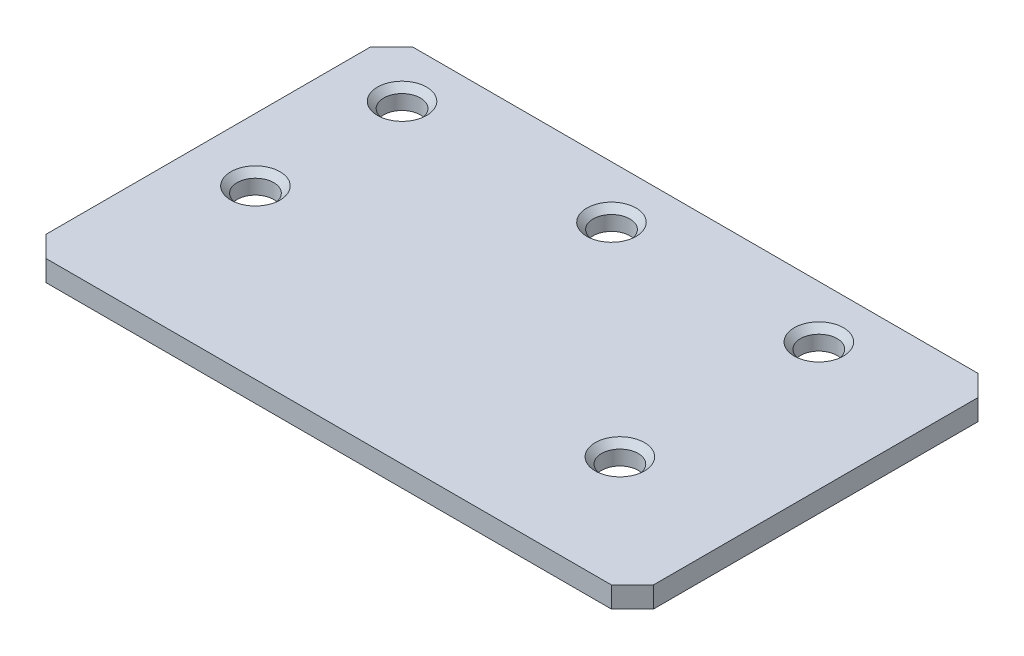
SolidWorks part; units mm, degrees
ref_plane "Front Plane" through (0, 0, 0) normal (0, 0, 1) x (1, 0, 0)
ref_plane "Top Plane" through (0, 0, 0) normal (0, 1, 0) x (1, 0, 0)
ref_plane "Right Plane" through (0, 0, 0) normal (1, 0, 0) x (0, 0, -1)
sketch "Sketch1" plane through (0, 0, 0) normal (0, 1, 0) x (1, 0, 0)
  line L1 (-29, -17.5) -> (29, -17.5)
  line L2 (-29, -17.5) -> (-29, 17.5)
  line L3 (-29, 17.5) -> (29, 17.5)
  line L4 (29, -17.5) -> (29, 17.5)
  line L5 (-29, -17.5) -> (29, 17.5) construction
  line L6 (-29, 17.5) -> (29, -17.5) construction
  point P0 (0, 0)
  dimension "D1" = 35
  dimension "D2" = 58
extrude "Boss-Extrude1" add sketch "Sketch1" along normal blind 2
hole_wizard "CSK for ST2.2 Cross recessed CTSK head tapping screws1" positions "Sketch2" profile "Sketch3" countersink size "ST2.2" standard "GB" end condition through all
sketch "Sketch2" plane through (0, 2, 0) normal (0, 1, 0) x (1, 0, 0)
  line L0 (-29, -17.5) -> (29, -17.5) construction
  line L1 (29, -17.5) -> (29, 17.5) construction
  point P0 (-23, 12.5)
  point P2 (-3, 12.5)
  point P4 (16.8, 12.5)
  point P6 (16.8, -6.5)
  point P8 (-23, -1.5)
  dimension "D1" = 11
  dimension "D2" = 19
  dimension "D3" = 12.2
  dimension "D4" = 19.8
  dimension "D5" = 20
  dimension "D6" = 16
sketch "Sketch3" plane through (-23, 2, -12.5) normal (1, 0, 0) x (0, 0, 1)
  line L0 (0, 0) -> (0, 2)
  line L1 (0, 2) -> (1.75, 2)
  line L2 (1.75, 2) -> (1.75, 0.6)
  line L3 (1.75, 0.6) -> (2.35, 0)
  line L5 (2.35, 0) -> (0, 0)
  line L6 (-1.75, 0.6) -> (-2.35, 0) construction
  line L11 (0, -6.35) -> (0, 107.95) construction
  dimension "Thru Hole Dia." = 3.5
  dimension "Thru Hole Depth" = 2
  dimension "Near C'Sink Dia." = 4.7
  dimension "Near C'Sink Angle" = 90
chamfer "Chamfer1" distance 2 angle 45 4 edges at (-29, 1, -17.5) (-29, 1, 17.5) (29, 1, 17.5) (29, 1, -17.5)
